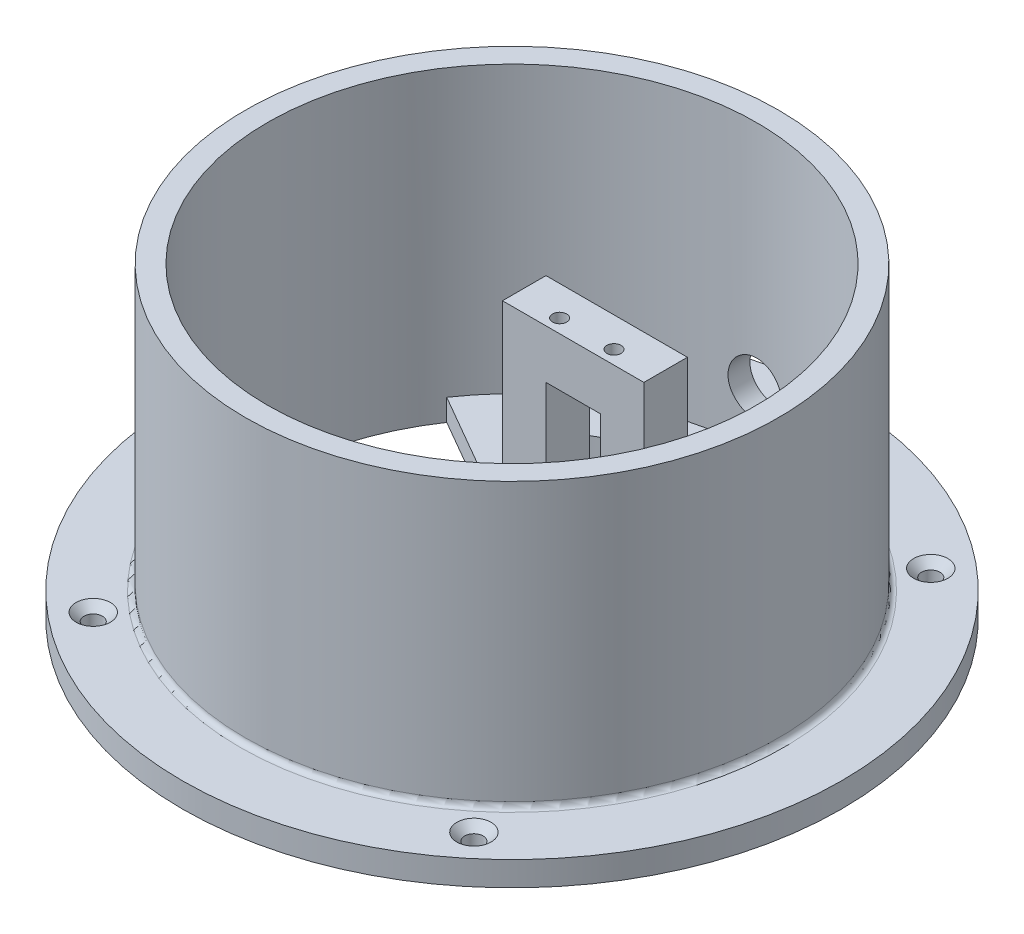
SolidWorks part; units mm, degrees
ref_plane "Front Plane" through (0, 0, 0) normal (0, 0, 1) x (1, 0, 0)
ref_plane "Top Plane" through (0, 0, 0) normal (0, 1, 0) x (1, 0, 0)
ref_plane "Right Plane" through (0, 0, 0) normal (1, 0, 0) x (0, 0, -1)
sketch "Sketch2" plane through (0, 0, 0) normal (0, 1, 0) x (1, 0, 0)
  circle A0 centre (0, 0) radius 60.625
  circle A1 centre (0, 0) radius 45
  dimension "D1" = 121.25
  dimension "D2" = 90
extrude "Boss-Extrude1" add sketch "Sketch2" along normal blind 4.5
sketch "Sketch3" plane through (0, 4.5, 0) normal (0, 1, 0) x (1, 0, 0)
  circle A2 centre (0, 0) radius 45 construction
  circle A4 centre (0, 0) radius 49
  circle A5 centre (0, 0) radius 49
  circle A6 centre (0, 0) radius 45
  dimension "D1" = 4
extrude "Boss-Extrude2" add sketch "Sketch3" along normal blind 52
sketch "Sketch4" plane through (0, 0, 0) normal (1, 0, 0) x (0, 0, -1)
  line L0 (-46.75, 38.5) -> (-31.75, 38.5)
  line L1 (-31.75, 38.5) -> (-31.75, 30.5)
  line L2 (-31.75, 30.5) -> (-46.75, 30.5)
  line L3 (-46.75, 30.5) -> (-46.75, 38.5)
  line L4 (-45, 56.5) -> (-45, 0)
  line L5 (-31.75, 30.5) -> (-45, 17.25)
  line L6 (-45, 0) -> (45, 0) construction
  line L7 (11.25, 38.5) -> (19.25, 38.5)
  line L8 (11.25, 38.5) -> (11.25, 0)
  line L9 (11.25, 0) -> (19.25, 0)
  line L10 (19.25, 38.5) -> (19.25, 0)
  line L11 (11.25, 38.5) -> (19.25, 0) construction
  line L12 (11.25, 0) -> (19.25, 38.5) construction
  line L13 (49, 56.5) -> (-49, 56.5) construction
  line L14 (45, 56.5) -> (-45, 56.5) construction
  point P8 (15.25, 19.25)
  dimension "D1" = 8
  dimension "D2" = 18
  dimension "D3" = 11.25
  dimension "D4" = 43
  dimension "D5" = 15
  dimension "D6" = 8
  dimension "D7" = 45
  dimension "D8" = 18
extrude "Boss-Extrude3" add sketch "Sketch4" along normal mid plane 26 contours L5 L2 L4 | L0 L4 L2 L1 | L10 L7 L8 L9
sketch "Sketch5" plane through (0, 0, 0) normal (0, 0, 1) x (1, 0, 0)
  line L6 (-5, 29.5) -> (5, 29.5)
  line L7 (-5, 29.5) -> (-5, 9.5)
  line L9 (5, 29.5) -> (5, 9.5)
  line L10 (-5, 29.5) -> (5, 9.5) construction
  line L11 (-5, 9.5) -> (5, 29.5) construction
  line L12 (13, 38.5) -> (-13, 38.5) construction
  line L14 (5, 9.5) -> (-5, 9.5)
  line L15 (49, 4.5) -> (-49, 4.5) construction
  point P0 (0, 19.5)
  point P5 (0, 9.5)
  dimension "D1" = 10
  dimension "D2" = 9
  dimension "D3" = 5
extrude "Cut-Extrude1" cut sketch "Sketch5" against normal blind 26
sketch "Sketch6" plane through (0, 0, -11.25) normal (0, 0, 1) x (1, 0, 0)
  line L0 (-60.625, 0) -> (60.625, 0) construction
  circle A0 centre (0, 14) radius 5
  dimension "D1" = 10
  dimension "D2" = 14
extrude "Cut-Extrude2" cut sketch "Sketch6" against normal through all
sketch "Sketch7" plane through (0, 38.5, 0) normal (0, 1, 0) x (1, 0, 0)
  line L0 (-5, -34.25) -> (5, -34.25) construction
  line L1 (-5, 13.75) -> (5, 13.75) construction
  line L2 (13, -31.75) -> (-13, -31.75) construction
  circle A0 centre (-5, 13.75) radius 1.3
  circle A1 centre (5, 13.75) radius 1.3
  circle A2 centre (-5, -34.25) radius 1.3
  circle A3 centre (5, -34.25) radius 1.3
  dimension "D1" = 2.6
  dimension "D2" = 5
  dimension "D3" = 10
  dimension "D4" = 10
  dimension "D5" = 2.5
  dimension "D6" = 48
extrude "Cut-Extrude3" cut sketch "Sketch7" against normal blind 7.2
sketch "Sketch8" plane through (0, 0, 0) normal (0, -1, 0) x (1, 0, 0)
  line L0 (13, -11.25) -> (-13, -11.25) construction
  line L1 (13, -11.25) -> (-13, -11.25)
  line L2 (-13, -11.25) -> (-37.2484, -25.2498)
  line L3 (0, 0) -> (0, -45) construction
  line L4 (13, -11.25) -> (37.2484, -25.2498)
  line L5 (-19.5167, -24.25) -> (-24.9065, -27.3618)
  line L6 (19.5167, -24.25) -> (24.9065, -27.3618)
  line L8 (-19.5167, -24.25) -> (19.5167, -24.25)
  line L9 (-10.8564, -19.25) -> (-24.9065, -27.3618) construction
  line L10 (10.8564, -19.25) -> (-10.8564, -19.25) construction
  line L11 (10.8564, -19.25) -> (24.9065, -27.3618) construction
  line L12 (13, -19.25) -> (-13, -19.25) construction
  circle A0 centre (0, 0) radius 45 construction
  arc A1 (-37.2484, -25.2498) -> (37.2484, -25.2498) centre (0, 0) ccw
  arc A2 (-24.9065, -27.3618) -> (24.9065, -27.3618) centre (0, 0) ccw
  dimension "D1" = 60
  dimension "D3" = 5
  dimension "D2" = 8
extrude "Boss-Extrude4" add sketch "Sketch8" against normal blind 4
sketch "Sketch9" plane through (0, 4.5, 0) normal (0, 1, 0) x (1, 0, 0)
  line L1 (-35, 42) -> (35, 42) construction
  line L2 (-35, 42) -> (-35, -42) construction
  line L3 (-35, -42) -> (35, -42) construction
  line L4 (35, 42) -> (35, -42) construction
  line L5 (-35, 42) -> (35, -42) construction
  line L6 (-35, -42) -> (35, 42) construction
  point P0 (0, 0)
  dimension "D1" = 84
  dimension "D2" = 70
hole_wizard "CSK for M3 Countersunk Flat Head Screw1" positions "3DSketch1" profile "Sketch10" countersink size "M3" standard "DIN"
sketch3d "3DSketch1"
  point P0 (-35, 4.5, -42)
  point P3 (35, 4.5, -42)
  point P6 (35, 4.5, 42)
  point P9 (-35, 4.5, 42)
sketch "Sketch10" plane through (-35, 4.5, -42) normal (1, 0, 0) x (0, 0, 1)
  line L0 (0, 0) -> (0, 45.4715)
  line L1 (0, 45.4715) -> (1.7, 44.45)
  line L2 (1.7, 44.45) -> (1.7, 1.45)
  line L3 (1.7, 1.45) -> (3.15, 0)
  line L5 (3.15, 0) -> (0, 0)
  line L6 (-1.7, 1.45) -> (-3.15, 0) construction
  line L10 (0, 45.4715) -> (-1.7, 44.45) construction
  line L11 (0, -6.35) -> (0, 107.95) construction
  dimension "Hole Dia." = 3.4
  dimension "Hole Depth" = 44.45
  dimension "Near C'Sink Dia." = 6.3
  dimension "Near C'Sink Angle" = 90
  dimension "Drill Angle" = 118
fillet "Fillet1" radius 1 1 edges at (0, 4.5, 49)
